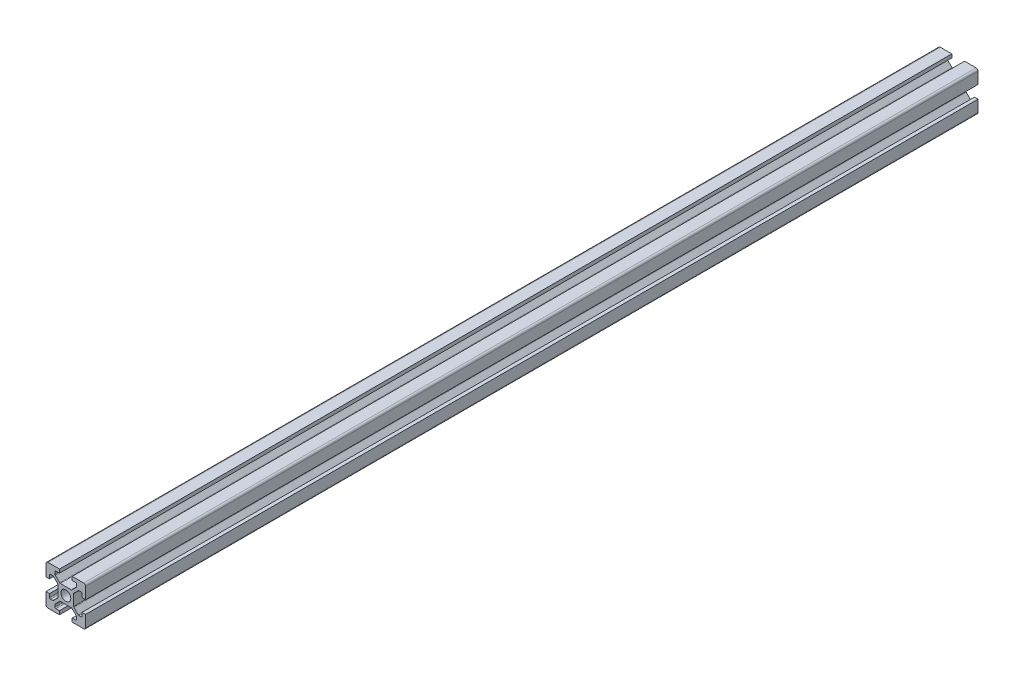
SolidWorks part; units mm, degrees
material "1060 Alloy"
ref_plane "Front Plane" through (0, 0, 0) normal (0, 0, 1) x (1, 0, 0)
ref_plane "Top Plane" through (0, 0, 0) normal (0, 1, 0) x (1, 0, 0)
ref_plane "Right Plane" through (0, 0, 0) normal (1, 0, 0) x (0, 0, -1)
sketch "Sketch1" plane through (0, 0, 0) normal (0, 0, 1) x (1, 0, 0)
  line L0 (20, 0) -> (-8.059, 28.059) construction
  line L1 (0, 0) -> (6.8, 0)
  line L2 (0, 0) -> (0, 6.8)
  line L3 (0, 20) -> (6.8, 20)
  line L4 (20, 0) -> (20, 6.8)
  line L5 (6.8, 20) -> (6.8, 18.2)
  line L6 (20, 20) -> (8.2322, 8.2322) construction
  line L7 (12.95, 6.1) -> (7.05, 6.1)
  line L8 (13.9, 7.05) -> (13.9, 12.95)
  line L9 (12.95, 13.9) -> (7.05, 13.9)
  line L10 (6.1, 7.05) -> (6.1, 12.95)
  line L11 (13.9, 6.1) -> (6.1, 13.9) construction
  line L12 (13.9, 13.9) -> (6.1, 6.1) construction
  line L13 (4.55, 16.4) -> (7.05, 13.9)
  line L14 (13.2, 18.2) -> (13.2, 20)
  line L15 (1.8, 6.8) -> (0, 6.8)
  line L16 (0, 13.2) -> (0, 20)
  line L17 (0, 13.2) -> (1.8, 13.2)
  line L18 (10, 10) -> (10, 13.9) construction
  line L19 (16.4, 4.55) -> (13.9, 7.05)
  line L20 (4.55, 16.4) -> (4.55, 18.2)
  line L21 (4.55, 18.2) -> (6.8, 18.2)
  line L22 (13.2, 18.2) -> (15.45, 18.2)
  line L23 (15.45, 18.2) -> (15.45, 16.4)
  line L24 (15.45, 16.4) -> (12.95, 13.9)
  line L25 (16.4, 4.55) -> (18.2, 4.55)
  line L26 (18.2, 4.55) -> (18.2, 6.8)
  line L27 (20, 6.8) -> (18.2, 6.8)
  line L28 (18.2, 13.2) -> (20, 13.2)
  line L29 (18.2, 13.2) -> (18.2, 15.45)
  line L30 (18.2, 15.45) -> (16.4, 15.45)
  line L31 (16.4, 15.45) -> (13.9, 12.95)
  line L32 (1.8, 4.55) -> (3.6, 4.55)
  line L33 (3.6, 15.45) -> (6.1, 12.95)
  line L34 (3.6, 15.45) -> (1.8, 15.45)
  line L35 (1.8, 15.45) -> (1.8, 13.2)
  line L36 (0, 13.2) -> (1.8, 13.2)
  line L37 (1.8, 6.8) -> (0, 6.8)
  line L38 (3.6, 4.55) -> (6.1, 7.05)
  line L39 (1.8, 6.8) -> (1.8, 4.55)
  line L40 (15.45, 3.6) -> (12.95, 6.1)
  line L41 (4.55, 3.6) -> (7.05, 6.1)
  line L42 (4.55, 1.8) -> (4.55, 3.6)
  line L43 (6.8, 1.8) -> (4.55, 1.8)
  line L44 (6.8, 1.8) -> (6.8, 0)
  line L45 (15.45, 3.6) -> (15.45, 1.8)
  line L46 (15.45, 1.8) -> (13.2, 1.8)
  line L47 (13.2, 0) -> (13.2, 1.8)
  line L48 (13.2, 20) -> (20, 20)
  line L49 (20, 13.2) -> (20, 20)
  line L50 (13.2, 0) -> (20, 0)
  line L51 (6.1, 6.1) -> (-5.5045, -5.5045) construction
  circle A0 centre (10, 10) radius 2.5
  point P25 (10, 16.4)
  point P39 (13.2, 19.1)
  point P46 (0.9, 6.8)
  dimension "D3" = 5
  dimension "D2" = 20
  dimension "D4" = 7.8
  dimension "D5" = 7.8
  dimension "D6" = 6.8
  dimension "D7" = 6.8
  dimension "D8" = 1.8
  dimension "D9" = 10.9
  dimension "D10" = 1.8
  dimension "D11" = 10.9
  dimension "D12" = 20
extrude "Boss-Extrude1" add sketch "Sketch1" along normal up to surface (450 mm away) contours L47 L50 L4 L27 L26 L25 L19 L8 L31 L30 L29 L28 L49 L48 L14 L22 L23 L24 L9 L13 L20 L21 L5 L3 L16 L17 L35 L34 L33 L10 L38 L32 L39 L15 L2 L1 L44 L43 L42 L41 L7 L40 L45 L46 A0
fillet "Fillet1" radius 1 4 edges at (20, 20, 225) (20, 0, 225) (0, 0, 225) (0, 20, 225)
fillet "Fillet2" radius 0.5 6 edges at (4.55, 18.2, 225) (4.55, 16.4, 225) (7.05, 13.9, 225) (15.45, 18.2, 225) (15.45, 16.4, 225) (12.95, 13.9, 225)
fillet "Fillet3" radius 0.5 6 edges at (18.2, 15.45, 225) (16.4, 15.45, 225) (13.9, 12.95, 225) (18.2, 4.55, 225) (13.9, 7.05, 225) (16.4, 4.55, 225)
fillet "Fillet4" radius 0.5 6 edges at (1.8, 15.45, 225) (3.6, 15.45, 225) (6.1, 12.95, 225) (3.6, 4.55, 225) (1.8, 4.55, 225) (6.1, 7.05, 225)
fillet "Fillet5" radius 0.5 6 edges at (7.05, 6.1, 225) (4.55, 3.6, 225) (4.55, 1.8, 225) (15.45, 1.8, 225) (15.45, 3.6, 225) (12.95, 6.1, 225)
